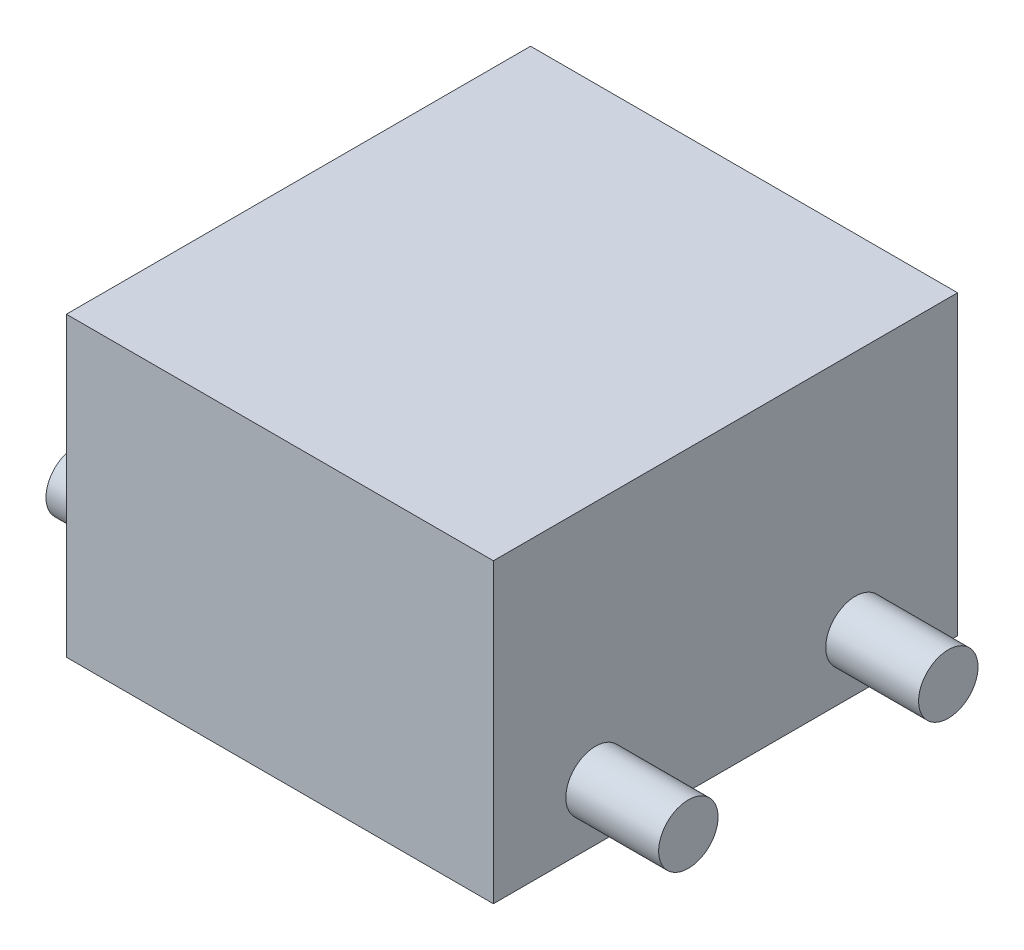
SolidWorks part; units mm, degrees
ref_plane "정면" through (0, 0, 0) normal (0, 0, 1) x (1, 0, 0)
ref_plane "윗면" through (0, 0, 0) normal (0, 1, 0) x (1, 0, 0)
ref_plane "우측면" through (0, 0, 0) normal (1, 0, 0) x (0, 0, -1)
sketch3d "3D스케치1"
  line L1 (-57.5, 0, 62.5) -> (57.5, 0, 62.5)
  line L2 (-57.5, 0, 62.5) -> (-57.5, 0, -62.5)
  line L3 (-57.5, 0, -62.5) -> (57.5, 0, -62.5)
  line L4 (57.5, 0, 62.5) -> (57.5, 0, -62.5)
  line L5 (-57.5, 0, 62.5) -> (57.5, 0, -62.5) construction
  line L6 (-57.5, 0, -62.5) -> (57.5, 0, 62.5) construction
  point P0 (0, 0, 0)
extrude "보스-돌출2" add sketch "3D스케치1" along direction (0, 1, 0) on the side against the normal blind 80
sketch "스케치1" plane through (0, 0, 0) normal (1, 0, 0) x (0, 0, -1)
  circle A0 centre (-35, 15) radius 8
extrude "보스-돌출3" add sketch "스케치1" along normal blind 82.5 and the other way blind 82.5
mirror "대칭 복사1" about plane through (0, 0, 0) normal (0, 0, 1) of "보스-돌출3", "보스-돌출2"
